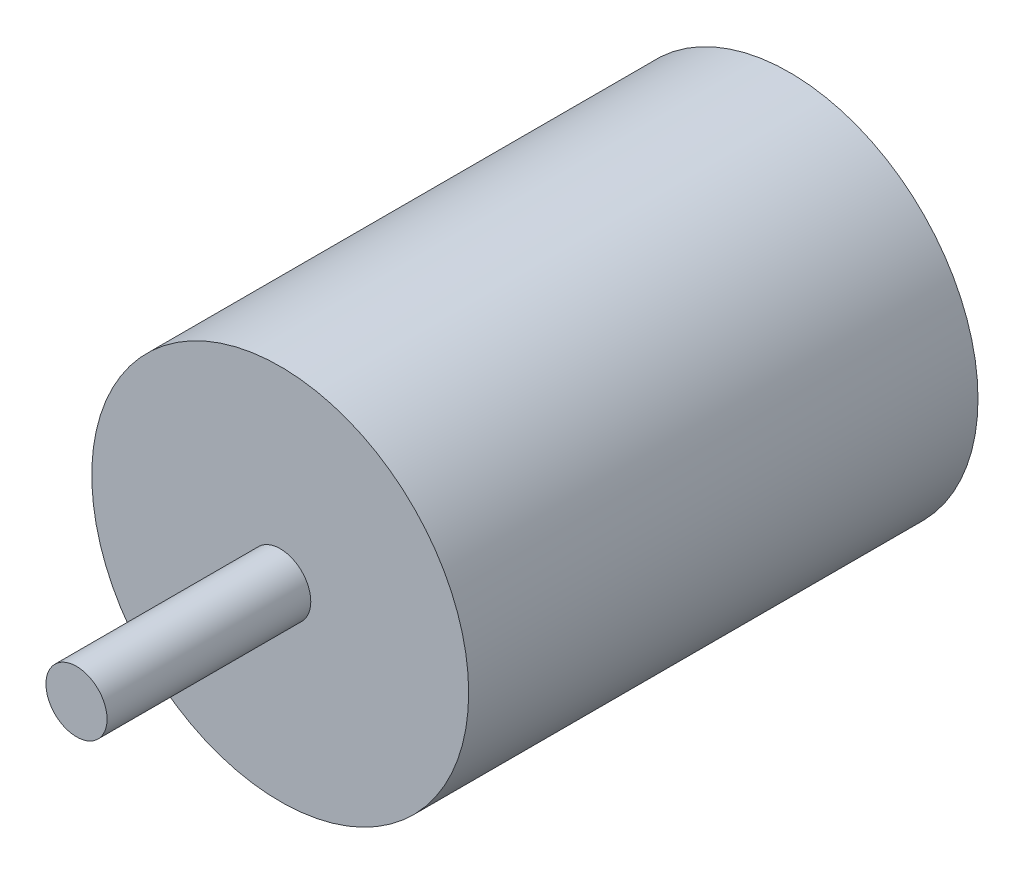
SolidWorks part; units mm, degrees
ref_plane "Front Plane" through (0, 0, 0) normal (0, 0, 1) x (1, 0, 0)
ref_plane "Top Plane" through (0, 0, 0) normal (0, 1, 0) x (1, 0, 0)
ref_plane "Right Plane" through (0, 0, 0) normal (1, 0, 0) x (0, 0, -1)
sketch "Sketch1" plane through (0, 0, 0) normal (0, 0, 1) x (1, 0, 0)
  circle A0 centre (0, 0) radius 18.5
  dimension "D1" = 37
extrude "Boss-Extrude1" add sketch "Sketch1" along normal blind 50
sketch "Sketch2" plane through (0, 0, 50) normal (0, 0, 1) x (1, 0, 0)
  circle A0 centre (0, 0) radius 3
  dimension "D1" = 6
extrude "Boss-Extrude2" add sketch "Sketch2" along normal blind 20
